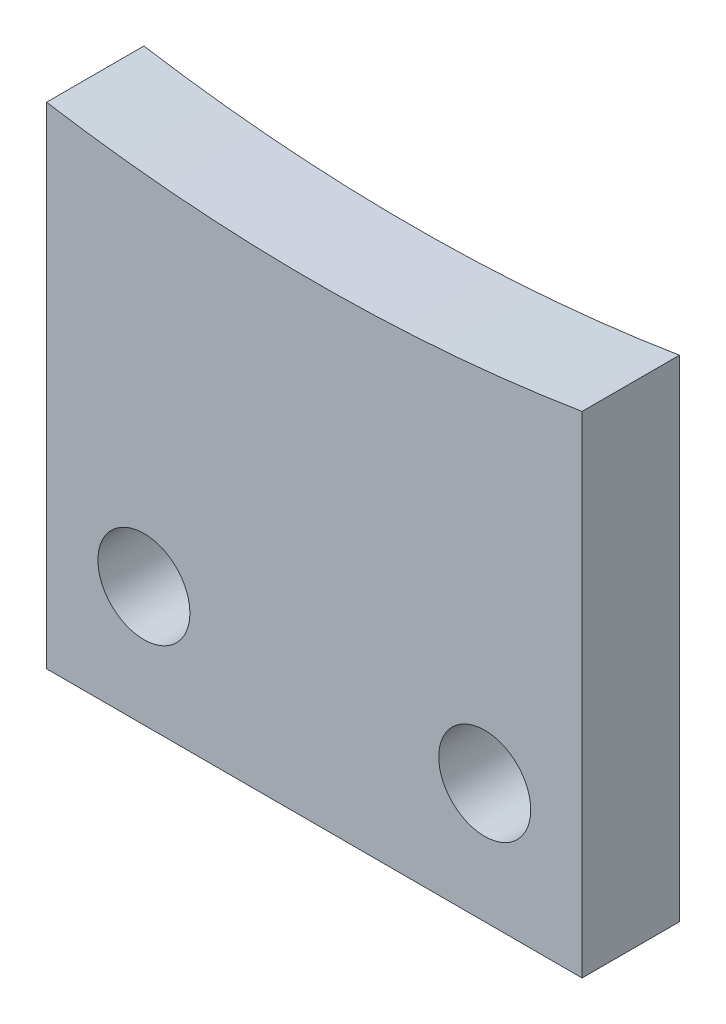
SolidWorks part; units mm, degrees
ref_plane "Front" through (0, 0, 0) normal (0, 0, 1) x (1, 0, 0)
ref_plane "Top" through (0, 0, 0) normal (0, 1, 0) x (1, 0, 0)
ref_plane "Right" through (0, 0, 0) normal (1, 0, 0) x (0, 0, -1)
sketch "Sketch1" plane through (0, 0, 0) normal (0, 0, 1) x (1, 0, 0)
  line L0 (0, -69.5002) -> (0, -65.5894)
  line L1 (0, -69.5002) -> (8.7313, -69.5002)
  line L2 (8.7313, -69.5002) -> (8.7312, -53.5002)
  line L3 (0, -69.5002) -> (-8.7312, -69.5002)
  line L4 (-8.7312, -69.5002) -> (-8.7312, -53.5002)
  line L5 (0, -65.5894) -> (5.5563, -65.5894)
  line L6 (0, -65.5894) -> (-5.5563, -65.5894)
  circle A0 centre (0, 0) radius 54.208
  circle A1 centre (-5.5563, -65.5894) radius 1.5
  circle A2 centre (5.5563, -65.5894) radius 1.5
  dimension "D1" = 8.7312
  dimension "D2" = 8.7312
  dimension "D3" = 3.9109
  dimension "D4" = 16
  dimension "D5" = 5.5563
  dimension "D6" = 5.5563
extrude "Boss-Extrude1" add sketch "Sketch1" along normal blind 3.175
